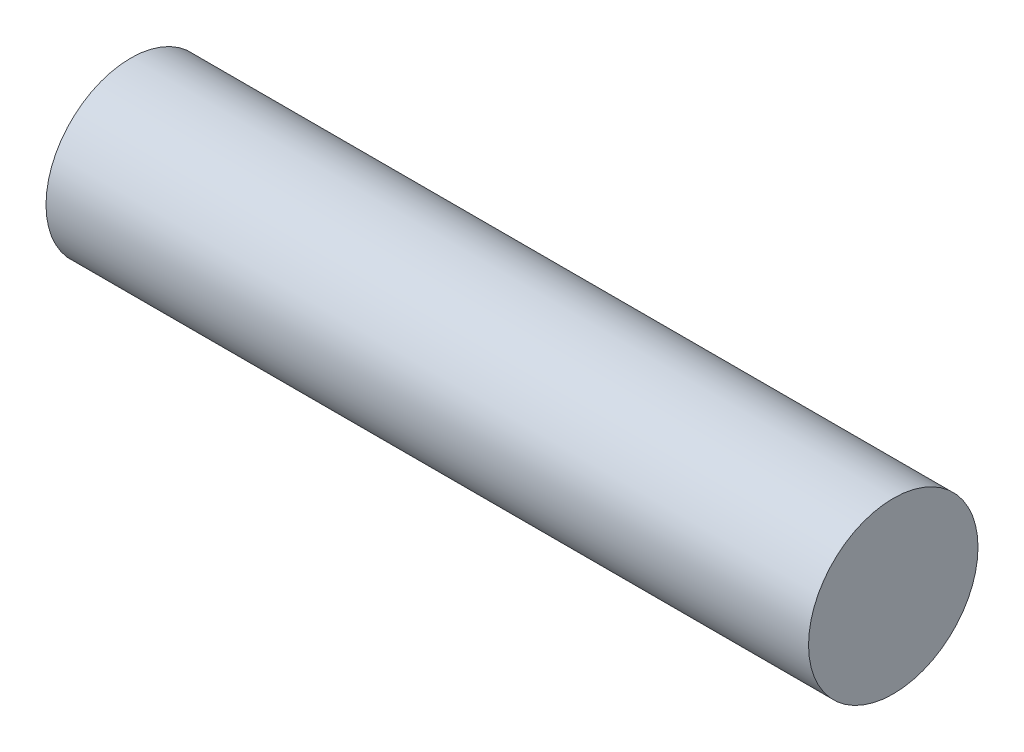
SolidWorks part; units mm, degrees
ref_plane "Front Plane" through (0, 0, 0) normal (0, 0, 1) x (1, 0, 0)
ref_plane "Top Plane" through (0, 0, 0) normal (0, 1, 0) x (1, 0, 0)
ref_plane "Right Plane" through (0, 0, 0) normal (1, 0, 0) x (0, 0, -1)
sketch "Sketch1" plane through (0, 0, 0) normal (1, 0, 0) x (0, 0, -1)
  circle A0 centre (0, 0) radius 2.5
  dimension "D1" = 5
extrude "Boss-Extrude1" add sketch "Sketch1" along normal blind 22.5
